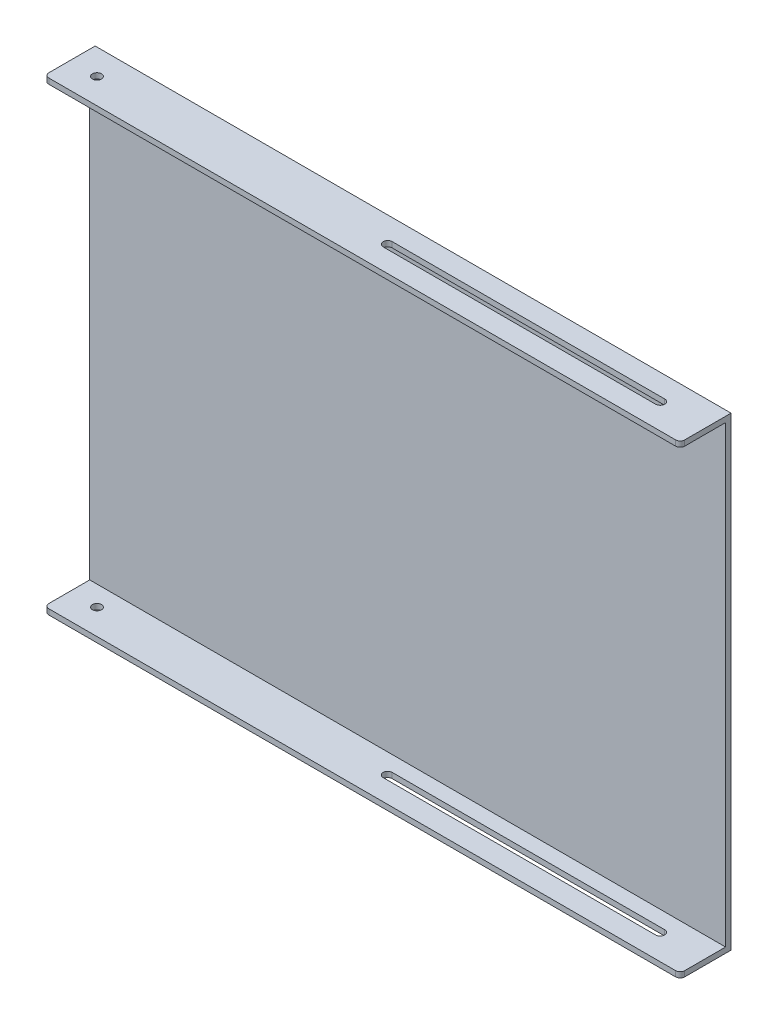
SolidWorks part; units mm, degrees
ref_plane "Front Plane" through (0, 0, 0) normal (0, 0, 1) x (1, 0, 0)
ref_plane "Top Plane" through (0, 0, 0) normal (0, 1, 0) x (1, 0, 0)
ref_plane "Right Plane" through (0, 0, 0) normal (1, 0, 0) x (0, 0, -1)
sketch "Sketch4" plane through (0, 0, 0) normal (0, 1, 0) x (1, 0, 0)
  line L0 (0, 0) -> (300, 0) construction
  line L1 (-350, 28) -> (350, 28)
  line L2 (-350, 28) -> (-350, -23)
  line L3 (-345, -28) -> (345, -28)
  line L4 (350, 28) -> (350, -23)
  line L5 (0, 5) -> (300, 5)
  line L6 (0, -5) -> (300, -5)
  arc A0 (0, 5) -> (0, -5) centre (0, 0) ccw
  arc A1 (300, -5) -> (300, 5) centre (300, 0) ccw
  circle A2 centre (-320, 0) radius 5
  arc A3 (345, -28) -> (350, -23) centre (345, -23) ccw
  arc A4 (-345, -28) -> (-350, -23) centre (-345, -23) cw
  point P0 (0, 0)
  point P8 (150, 0)
  dimension "D7" = 10
  dimension "D10" = 5
  dimension "D1" = 350
  dimension "D2" = 28
  dimension "D3" = 350
  dimension "D4" = 28
  dimension "D5" = 300
  dimension "D6" = 5
  dimension "D8" = 30
  dimension "D9" = 28
extrude "Boss-Extrude2" add sketch "Sketch4" along normal mid plane 512
sketch "Sketch5" plane through (350, 0, 0) normal (1, 0, 0) x (0, 0, -1)
  line L0 (-28, 256) -> (-28, -256) construction
  line L1 (-28, 250) -> (-28, -250)
  line L12 (-28, -250) -> (22, -250)
  line L13 (22, -250) -> (22, 250)
  line L14 (22, 250) -> (-28, 250)
  point P9 (-3, -250)
extrude "Cut-Extrude2" cut sketch "Sketch5" against normal through all both and the other way through all
